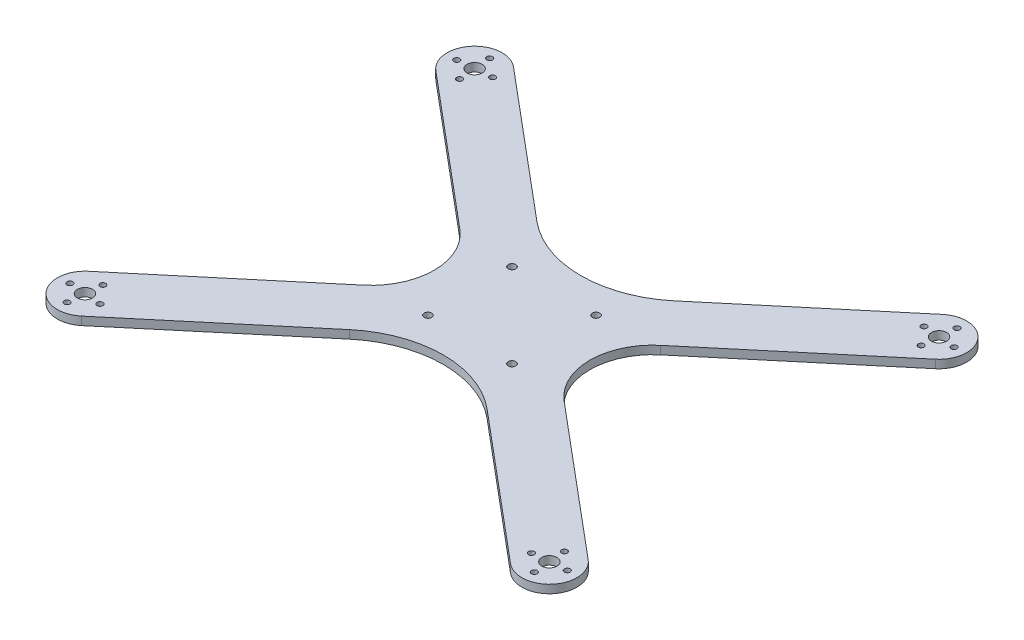
SolidWorks part; units mm, degrees
material "Custom Plastic"
ref_plane "Front Plane" through (0, 0, 0) normal (0, 0, 1) x (1, 0, 0)
ref_plane "Top Plane" through (0, 0, 0) normal (0, 1, 0) x (1, 0, 0)
ref_plane "Right Plane" through (0, 0, 0) normal (1, 0, 0) x (0, 0, -1)
sketch "Sketch1" plane through (0, 0, 0) normal (0, 1, 0) x (1, 0, 0)
  line L1 (-36.375, -26.375) -> (36.375, -26.375) construction
  line L2 (-36.375, -26.375) -> (-36.375, 26.375) construction
  line L3 (-36.375, 26.375) -> (36.375, 26.375) construction
  line L4 (36.375, -26.375) -> (36.375, 26.375) construction
  line L5 (-36.375, -26.375) -> (36.375, 26.375) construction
  line L6 (-36.375, 26.375) -> (36.375, -26.375) construction
  circle A0 centre (-36.375, 26.375) radius 1.25
  circle A4 centre (36.375, 26.375) radius 1.25
  circle A5 centre (36.375, -26.375) radius 1.25
  circle A6 centre (-36.375, -26.375) radius 1.25
  point P8 (0, 0)
  dimension "D1" = 2.5
  dimension "D2" = 52.75
  dimension "D3" = 72.75
sketch "Sketch2" plane through (0, 0, 0) normal (0, 1, 0) x (1, 0, 0)
  line L0 (0, 0) -> (-84.2649, 70.7066) construction
  line L1 (0, 0) -> (84.2649, 70.7066) construction
  line L2 (0, 0) -> (84.2649, -70.7066) construction
  line L3 (0, 0) -> (-84.2649, -70.7066) construction
  line L4 (-30, 0) -> (30, 0) construction
  line L5 (-77.837, 78.3671) -> (-90.6928, 63.0462) construction
  line L10 (36.4129, -30.5541) -> (-32.6921, 27.4319) construction
  line L12 (0, 21.0062) -> (0, -21.0062) construction
  line L13 (-90.6928, 63.0462) -> (-36.4129, 17.5)
  line L14 (90.6928, -63.0462) -> (36.4129, -17.5)
  line L15 (-90.2421, 70.1837) -> (-78.2877, 71.2296) construction
  line L16 (-84.7878, 76.6838) -> (-83.742, 64.7295) construction
  line L17 (-90.6928, -63.0462) -> (-77.837, -78.3671) construction
  line L18 (-90.6928, -63.0462) -> (-36.4129, -17.5)
  line L19 (-77.837, -78.3671) -> (-25, -34.0316)
  line L21 (25, 34.0316) -> (77.837, 78.3671)
  line L22 (-25, 34.0316) -> (-77.837, 78.3671)
  line L23 (36.4129, 17.5) -> (90.6928, 63.0462)
  line L24 (25, -34.0316) -> (77.837, -78.3671)
  arc A3 (-77.837, 78.3671) -> (-90.6928, 63.0462) centre (-84.2649, 70.7066) ccw
  circle A4 centre (-84.7878, 76.6838) radius 1.05
  circle A5 centre (-78.2877, 71.2296) radius 1.05
  circle A6 centre (-83.742, 64.7295) radius 1.05
  circle A7 centre (-90.2421, 70.1837) radius 1.05
  circle A8 centre (-84.2649, 70.7066) radius 2.75
  circle A9 centre (-84.7878, -76.6838) radius 1.05
  circle A10 centre (-83.742, -64.7295) radius 1.05
  circle A11 centre (-90.2421, -70.1837) radius 1.05
  circle A12 centre (-84.2649, -70.7066) radius 2.75
  circle A13 centre (-78.2877, -71.2296) radius 1.05
  arc A14 (-77.837, -78.3671) -> (-90.6928, -63.0462) centre (-84.2649, -70.7066) cw
  arc A15 (77.837, -78.3671) -> (90.6928, -63.0462) centre (84.2649, -70.7066) ccw
  circle A16 centre (78.2877, -71.2296) radius 1.05
  circle A17 centre (84.2649, -70.7066) radius 2.75
  circle A18 centre (90.2421, -70.1837) radius 1.05
  circle A19 centre (83.742, -64.7295) radius 1.05
  circle A20 centre (84.7878, -76.6838) radius 1.05
  circle A21 centre (84.2649, 70.7066) radius 2.75
  circle A22 centre (90.2421, 70.1837) radius 1.05
  circle A23 centre (83.742, 64.7295) radius 1.05
  circle A24 centre (78.2877, 71.2296) radius 1.05
  circle A25 centre (84.7878, 76.6838) radius 1.05
  arc A26 (77.837, 78.3671) -> (90.6928, 63.0462) centre (84.2649, 70.7066) cw
  arc A27 (-36.4129, 17.5) -> (-36.4129, -17.5) centre (-51.0972, 0) cw
  arc A28 (-25, -34.0316) -> (25, -34.0316) centre (0, -63.8254) cw
  arc A29 (36.4129, -17.5) -> (36.4129, 17.5) centre (51.0972, 0) cw
  arc A30 (25, 34.0316) -> (-25, 34.0316) centre (0, 63.8254) cw
  point P29 (-84.2649, 70.7066)
  point P34 (-84.2649, 70.7066)
  point P35 (-84.2649, 70.7066)
  point P61 (84.2649, 70.7066)
  point P63 (0, 0)
  dimension "D5" = 20
  dimension "D7" = 2.1
  dimension "D10" = 5.5
  dimension "D2" = 50
  dimension "D3" = 40
  dimension "D4" = 110
  dimension "D6" = 35
  dimension "D8" = 12
  dimension "D9" = 45
extrude "Boss-Extrude2" add sketch "Sketch2" along normal blind 3
sketch "Sketch4" plane through (0, 0, 0) normal (0, 1, 0) x (1, 0, 0)
  line L1 (-15.25, -15.25) -> (15.25, -15.25) construction
  line L2 (-15.25, -15.25) -> (-15.25, 15.25) construction
  line L3 (-15.25, 15.25) -> (15.25, 15.25) construction
  line L4 (15.25, -15.25) -> (15.25, 15.25) construction
  line L5 (-15.25, -15.25) -> (15.25, 15.25) construction
  line L6 (-15.25, 15.25) -> (15.25, -15.25) construction
  circle A0 centre (-15.25, 15.25) radius 1.375
  circle A1 centre (15.25, -15.25) radius 1.375
  circle A2 centre (-15.25, -15.25) radius 1.375
  circle A3 centre (15.25, 15.25) radius 1.375
  point P5 (0, 0)
  dimension "D2" = 2.75
  dimension "D1" = 30.5
extrude "Cut-Extrude1" cut sketch "Sketch4" along normal blind 3
